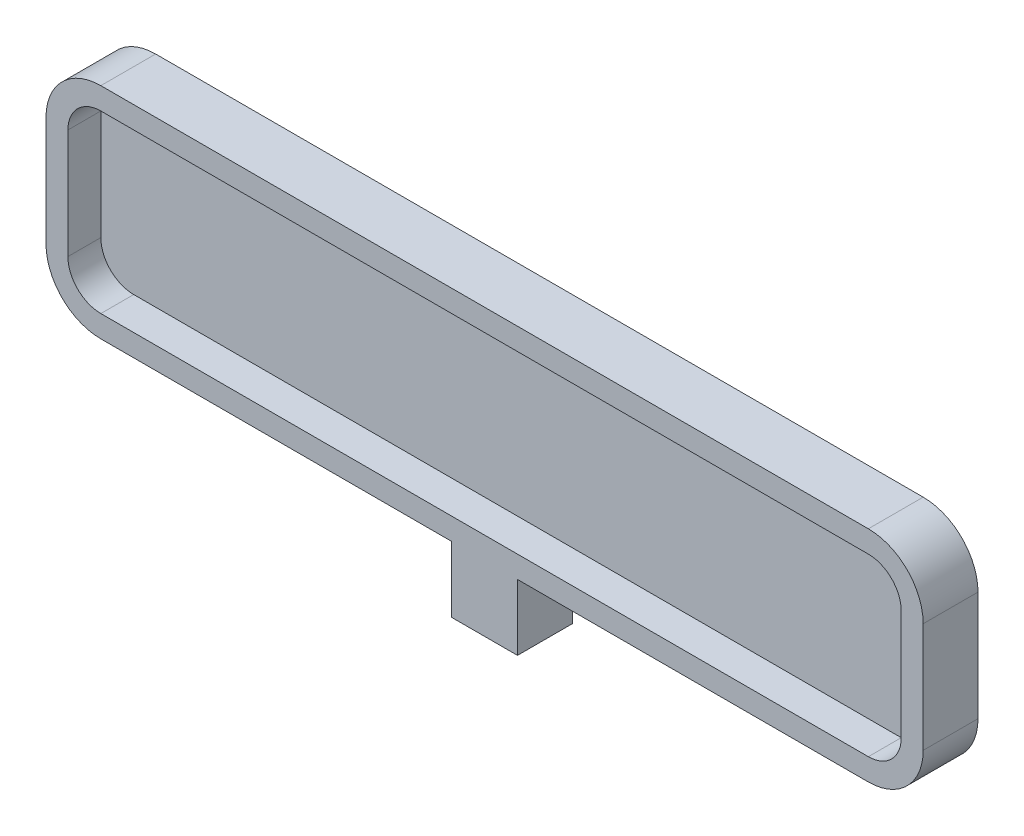
SolidWorks part; units mm, degrees
ref_plane "Front Plane" through (0, 0, 0) normal (0, 0, 1) x (1, 0, 0)
ref_plane "Top Plane" through (0, 0, 0) normal (0, 1, 0) x (1, 0, 0)
ref_plane "Right Plane" through (0, 0, 0) normal (1, 0, 0) x (0, 0, -1)
sketch "Sketch1" plane through (0, 0, 0) normal (0, 0, 1) x (1, 0, 0)
  line L1 (40, -10) -> (-40, -10)
  line L2 (40, -10) -> (40, 10)
  line L3 (40, 10) -> (-40, 10)
  line L4 (-40, -10) -> (-40, 10)
  line L5 (40, -10) -> (-40, 10) construction
  line L6 (40, 10) -> (-40, -10) construction
  point P0 (0, 0)
  dimension "D1" = 80
  dimension "D2" = 20
extrude "Boss-Extrude1" add sketch "Sketch1" along normal blind 5
fillet "Fillet1" radius 5 4 edges at (40, 10, 2.5) (40, -10, 2.5) (-40, -10, 2.5) (-40, 10, 2.5)
shell "Shell1" thickness 2
sketch "Sketch2" plane through (0, -10, 0) normal (0, -1, 0) x (1, 0, 0)
  line L6 (-3, 0) -> (3, 0)
  line L7 (-3, 0) -> (-3, 5)
  line L8 (3, 0) -> (3, 5)
  line L9 (-3, 5) -> (3, 5)
  line L10 (-35, 0) -> (35, 0) construction
  line L12 (0, 0) -> (0, 5) construction
  dimension "D1" = 6
  dimension "D2" = 5
extrude "Boss-Extrude2" add sketch "Sketch2" along normal blind 6
sketch "Sketch3" plane through (0, -16, 0) normal (0, -1, 0) x (1, 0, 0)
  line L0 (0, 0) -> (0, 5) construction
  line L1 (-3, 0) -> (3, 0) construction
  line L2 (3, 5) -> (-3, 5) construction
  line L3 (-3, 2.5) -> (3, 2.5) construction
  line L6 (-3, 5) -> (-3, 0) construction
  line L7 (3, 0) -> (3, 5) construction
  circle A0 centre (0, 2.5) radius 1.425
  point P14 (0, 0)
  dimension "D1" = 2.85
extrude "Cut-Extrude1" cut sketch "Sketch3" against normal blind 4
